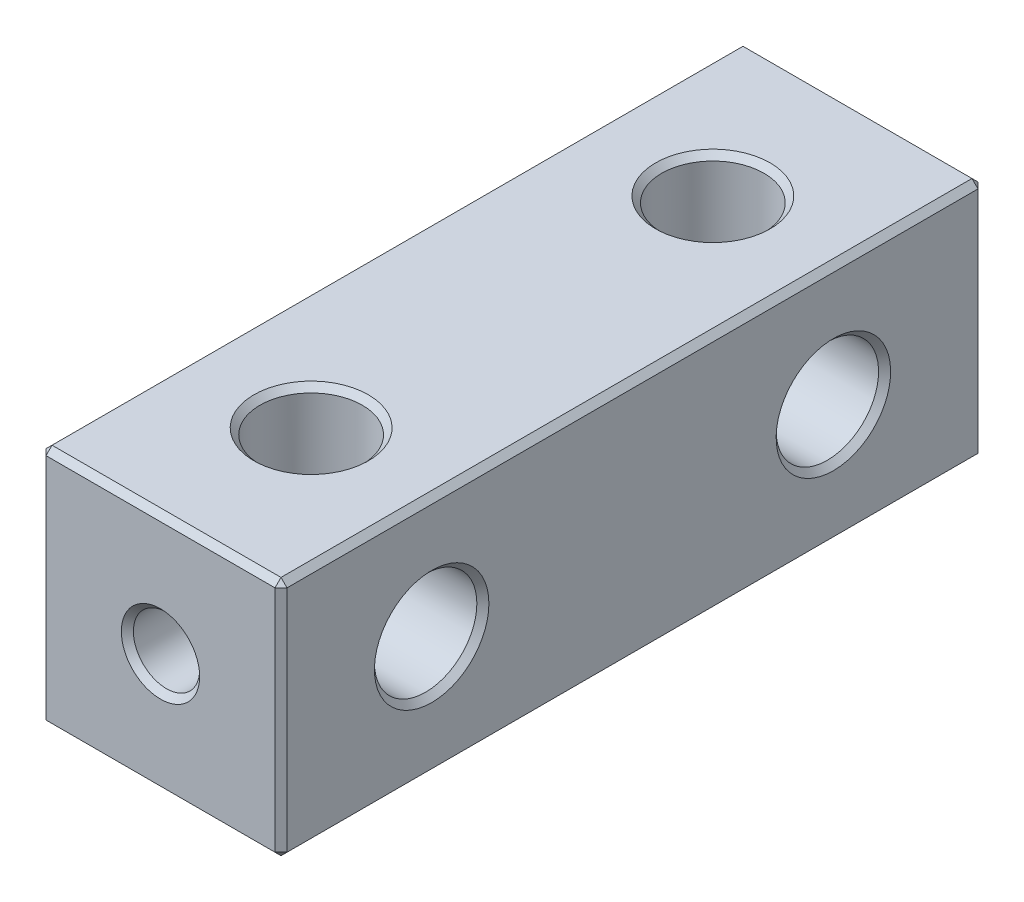
SolidWorks part; units mm, degrees
ref_plane "前视基准面" through (0, 0, 0) normal (0, 0, 1) x (1, 0, 0)
ref_plane "上视基准面" through (0, 0, 0) normal (0, 1, 0) x (1, 0, 0)
ref_plane "右视基准面" through (0, 0, 0) normal (1, 0, 0) x (0, 0, -1)
sketch "草图1" plane through (0, 0, 0) normal (0, 0, 1) x (1, 0, 0)
  line L1 (-6, 6) -> (6, 6)
  line L2 (-6, 6) -> (-6, -6)
  line L3 (-6, -6) -> (6, -6)
  line L4 (6, 6) -> (6, -6)
  line L5 (-6, 6) -> (6, -6) construction
  line L6 (-6, -6) -> (6, 6) construction
  point P0 (0, 0)
  dimension "D1" = 12
extrude "凸台-拉伸1" add sketch "草图1" along normal mid plane 35
hole_wizard "Ø5.1 (5.1) 直径孔1" positions "草图2" profile "草图3" hole size "Ø5.1" standard "GB" end condition through all
sketch "草图2" plane through (6, 0, 0) normal (1, 0, 0) x (0, 0, -1)
  line L0 (0, 0) -> (0, 50000) construction
  line L1 (-17.5, 6) -> (17.5, 6) construction
  line L2 (0, 0) -> (50000, 0) construction
  point P0 (-10, 0)
  point P2 (10, 0)
  point P10 (0, 6)
  dimension "D1" = 20
sketch "草图3" plane through (6, 0, 10) normal (0, 1, 0) x (0, 0, -1)
  line L0 (0, 0) -> (0, 12)
  line L1 (0, 12) -> (2.55, 12)
  line L2 (2.55, 12) -> (2.55, 0)
  line L5 (2.55, 0) -> (0, 0)
  line L11 (0, -6.35) -> (0, 107.95) construction
  dimension "通孔孔直径" = 5.1
  dimension "通孔孔深度" = 12
hole_wizard "Ø5.1 (5.1) 直径孔2" positions "草图4" profile "草图5" hole size "Ø5.1" standard "GB" end condition through all
sketch "草图4" plane through (0, 6, 0) normal (0, 1, 0) x (1, 0, 0)
  line L0 (0, 0) -> (0, 50000) construction
  line L1 (0, 0) -> (-50000, 0) construction
  point P0 (0, -10)
  point P2 (0, 10)
  dimension "D1" = 20
sketch "草图5" plane through (0, 6, 10) normal (1, 0, 0) x (0, 0, 1)
  line L0 (0, 0) -> (0, 12)
  line L1 (0, 12) -> (2.55, 12)
  line L2 (2.55, 12) -> (2.55, 0)
  line L5 (2.55, 0) -> (0, 0)
  line L11 (0, -6.35) -> (0, 107.95) construction
  dimension "通孔孔直径" = 5.1
  dimension "通孔孔深度" = 12
hole_wizard "M4 螺纹孔1" positions "草图6" profile "草图7" tap size "M4" standard "GB"
sketch "草图6" plane through (0, 0, 17.5) normal (0, 0, 1) x (1, 0, 0)
  point P0 (0, 0)
sketch "草图7" plane through (0, 0, 17.5) normal (1, 0, 0) x (0, -1, 0)
  line L0 (0, 0) -> (0, 4.95)
  line L1 (0, 4.95) -> (1.65, 4.95)
  line L2 (1.65, 4.95) -> (1.65, 0)
  line L5 (1.65, 0) -> (0, 0)
  line L11 (0, -6.35) -> (0, 107.95) construction
  dimension "通孔螺纹孔钻头直径" = 3.3
  dimension "通孔螺纹孔钻头深度" = 4.95
cosmetic thread "孔螺蚊线1"
hole_wizard "M4 螺纹孔2" positions "草图8" profile "草图9" tap size "M4" standard "GB"
sketch "草图8" plane through (0, 0, -17.5) normal (0, 0, -1) x (-1, 0, 0)
  point P0 (0, 0)
sketch "草图9" plane through (0, 0, -17.5) normal (1, 0, 0) x (0, 1, 0)
  line L0 (0, 0) -> (0, 4.95)
  line L1 (0, 4.95) -> (1.65, 4.95)
  line L2 (1.65, 4.95) -> (1.65, 0)
  line L5 (1.65, 0) -> (0, 0)
  line L11 (0, -6.35) -> (0, 107.95) construction
  dimension "通孔螺纹孔钻头直径" = 3.3
  dimension "通孔螺纹孔钻头深度" = 4.95
cosmetic thread "孔螺蚊线2"
chamfer "倒角1" distance 0.3 angle 45 22 edges at (-1.65, 0, -17.5) (1.65, 0, 17.5) (6, 0, -12.55) (6, 0, 7.45) (0, -6, -7.45) (0, -6, 12.55) (-6, 0, -12.55) (-6, 0, 7.45) (6, 0, 17.5) (6, 0, -17.5) (0, -6, 17.5) (6, -6, 0) (0, -6, -17.5) (-6, 0, 17.5) (-6, -6, 0) (-6, 0, -17.5) (6, 6, 0) (0, 6, 17.5) (-6, 6, 0) (0, 6, -17.5) (0, 6, -7.45) (0, 6, 12.55)
